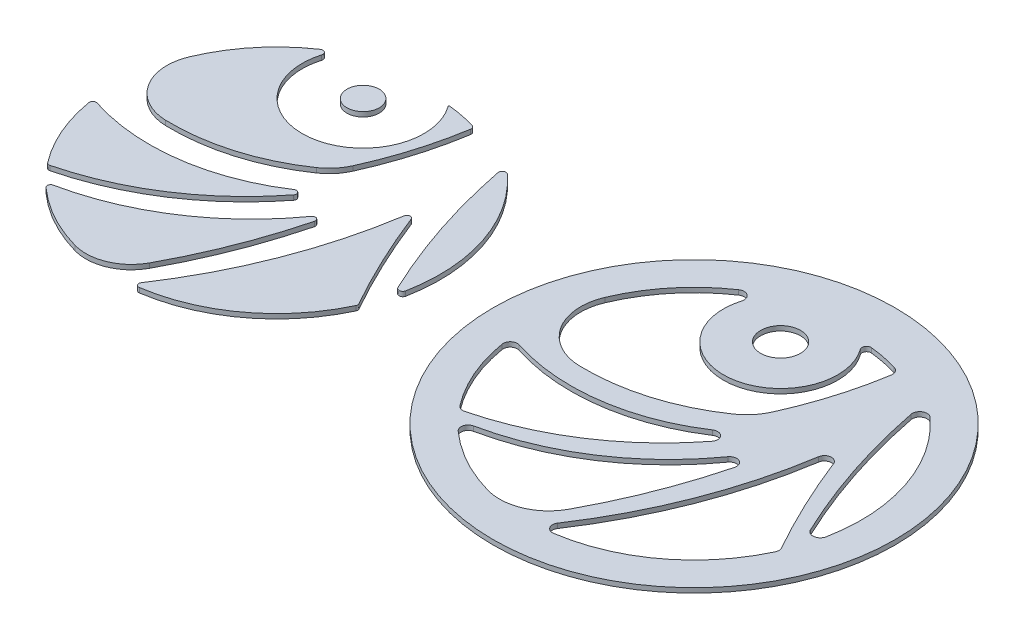
SolidWorks part; units mm, degrees
ref_plane "Front Plane" through (0, 0, 0) normal (0, 0, 1) x (1, 0, 0)
ref_plane "Top Plane" through (0, 0, 0) normal (0, 1, 0) x (1, 0, 0)
ref_plane "Right Plane" through (0, 0, 0) normal (1, 0, 0) x (0, 0, -1)
sketch "Sketch1" plane through (0, 0, 0) normal (0, 1, 0) x (1, 0, 0)
  line L0 (0, 0) -> (0, 6.0566) construction
  line L1 (44.4871, -0.2174) -> (44.4871, 5.8392) construction
  arc A34 (-4.7592, -16.858) -> (1.0322, -14.4089) centre (-3.3927, -12.0175) ccw construction
  arc A35 (11.8017, 12.9446) -> (17.1937, -3.3496) centre (0, 0) cw construction
  circle A36 centre (-2.9281, 12.0992) radius 1.9122 construction
  arc A37 (16.0926, -3.4891) -> (17.1937, -3.3496) centre (16.6201, -3.2378) ccw construction
  arc A38 (-8.936, 13.8547) -> (2.1496, 15.7589) centre (-2.9281, 12.0992) ccw construction
  arc A39 (10.8347, 12.3997) -> (16.0926, -3.4891) centre (76.7619, 25.4016) ccw construction
  arc A40 (-11.4052, -0.5681) -> (-16.15, 6.7839) centre (-11.2626, 4.731) cw construction
  arc A41 (2.9045, 5.3154) -> (5.7854, 14.9411) centre (-31.9799, 21.0002) ccw construction
  arc A42 (-11.4052, -0.5681) -> (1.0701, 3.1191) centre (-10.8394, 20.4655) ccw construction
  arc A43 (2.9045, 5.3154) -> (1.0701, 3.1191) centre (-1.9303, 7.4893) cw construction
  arc A44 (5.3743, 15.594) -> (2.3971, 16.1859) centre (0.6618, -0.327) ccw construction
  arc A45 (10.8347, 12.3997) -> (11.8017, 12.9446) centre (11.408, 12.5128) cw construction
  arc A46 (-8.936, 13.8547) -> (-9.8246, 14.5024) centre (-9.4969, 14.0186) ccw construction
  arc A47 (5.3743, 15.594) -> (5.7854, 14.9411) centre (5.2085, 15.0337) cw construction
  arc A48 (2.1496, 15.7589) -> (2.3971, 16.1859) centre (2.3689, 15.917) cw construction
  arc A49 (4.9905, -1.3518) -> (5.9661, -1.8054) centre (5.436, -1.6696) cw construction
  arc A50 (1.6673, 0.2398) -> (2.4003, -0.5531) centre (1.9681, -0.2174) cw construction
  arc A51 (10.8773, 3.6514) -> (9.8271, 3.5354) centre (10.3679, 3.4515) ccw construction
  arc A52 (15.8695, -6.8767) -> (15.8887, -7.3751) centre (15.3923, -7.1447) cw construction
  arc A53 (2.0596, -16.4793) -> (2.5965, -17.3234) centre (2.5154, -16.7822) ccw construction
  arc A54 (-11.4455, -12.0949) -> (-11.6987, -13.0378) centre (-11.3332, -12.6305) ccw construction
  arc A55 (-13.3427, -10.8431) -> (-13.9114, -10.6451) centre (-13.4768, -10.3125) cw construction
  arc A56 (-16.5773, -2.2267) -> (-17.2859, -2.8359) centre (-16.7458, -2.7473) ccw construction
  arc A57 (15.8887, -7.3751) -> (2.5965, -17.3234) centre (0, 0) cw construction
  arc A58 (-4.7592, -16.858) -> (-11.6987, -13.0378) centre (0, 0) cw construction
  arc A59 (-13.9114, -10.6451) -> (-17.2859, -2.8359) centre (0, 0) cw construction
  arc A60 (9.8271, 3.5354) -> (2.0596, -16.4793) centre (-39.5789, 11.1947) cw construction
  arc A61 (2.4003, -0.5531) -> (-13.3427, -10.8431) centre (-20.4231, 17.1773) cw construction
  arc A62 (1.6673, 0.2398) -> (-16.5773, -2.2267) centre (-10.0245, 18.0137) cw construction
  arc A63 (5.9661, -1.8054) -> (1.0322, -14.4089) centre (-47.7586, 11.959) cw construction
  arc A64 (4.9905, -1.3518) -> (-11.4455, -12.0949) centre (-16.9851, 14.3246) cw construction
  arc A65 (15.8695, -6.8767) -> (10.8773, 3.6514) centre (89.6755, 34.5677) cw construction
  arc A66 (-16.15, 6.7839) -> (-9.8246, 14.5024) centre (0, 0) cw construction
  arc A68 (39.7279, -17.0755) -> (45.5192, -14.6263) centre (41.0944, -12.235) ccw construction
  arc A69 (56.2888, 12.7272) -> (61.6808, -3.567) centre (44.4871, -0.2174) cw construction
  circle A70 centre (41.5589, 11.8818) radius 1.9122 construction
  arc A71 (60.5796, -3.7065) -> (61.6808, -3.567) centre (61.1072, -3.4553) ccw construction
  arc A72 (35.5511, 13.6373) -> (46.6366, 15.5415) centre (41.5589, 11.8818) ccw construction
  arc A73 (55.3218, 12.1823) -> (60.5796, -3.7065) centre (121.249, 25.1842) ccw construction
  arc A74 (33.0819, -0.7855) -> (28.3371, 6.5665) centre (33.2244, 4.5136) cw construction
  arc A75 (47.3916, 5.098) -> (50.2725, 14.7237) centre (12.5072, 20.7828) ccw construction
  arc A76 (33.0819, -0.7855) -> (45.5572, 2.9017) centre (33.6477, 20.2481) ccw construction
  arc A77 (47.3916, 5.098) -> (45.5572, 2.9017) centre (42.5568, 7.2719) cw construction
  arc A78 (49.8614, 15.3766) -> (46.8842, 15.9685) centre (45.1488, -0.5444) ccw construction
  arc A79 (55.3218, 12.1823) -> (56.2888, 12.7272) centre (55.8951, 12.2954) cw construction
  arc A80 (35.5511, 13.6373) -> (34.6625, 14.285) centre (34.9902, 13.8012) ccw construction
  arc A81 (49.8614, 15.3766) -> (50.2725, 14.7237) centre (49.6955, 14.8163) cw construction
  arc A82 (46.6366, 15.5415) -> (46.8842, 15.9685) centre (46.8559, 15.6996) cw construction
  arc A83 (49.4775, -1.5692) -> (50.4532, -2.0229) centre (49.923, -1.887) cw construction
  arc A84 (46.1544, 0.0224) -> (46.8873, -0.7706) centre (46.4552, -0.4348) cw construction
  arc A85 (55.3644, 3.434) -> (54.3142, 3.3179) centre (54.855, 3.2341) ccw construction
  arc A86 (60.3566, -7.0941) -> (60.3758, -7.5925) centre (59.8794, -7.3621) cw construction
  arc A87 (46.5467, -16.6967) -> (47.0836, -17.5409) centre (47.0025, -16.9996) ccw construction
  arc A88 (33.0415, -12.3123) -> (32.7884, -13.2552) centre (33.1538, -12.8479) ccw construction
  arc A89 (31.1444, -11.0605) -> (30.5757, -10.8625) centre (31.0103, -10.5299) cw construction
  arc A90 (27.9098, -2.4441) -> (27.2012, -3.0533) centre (27.7412, -2.9647) ccw construction
  arc A91 (60.3758, -7.5925) -> (47.0836, -17.5409) centre (44.4871, -0.2174) cw construction
  arc A92 (39.7279, -17.0755) -> (32.7884, -13.2552) centre (44.4871, -0.2174) cw construction
  arc A93 (30.5757, -10.8625) -> (27.2012, -3.0533) centre (44.4871, -0.2174) cw construction
  arc A94 (54.3142, 3.3179) -> (46.5467, -16.6967) centre (4.9081, 10.9773) cw construction
  arc A95 (46.8873, -0.7706) -> (31.1444, -11.0605) centre (24.064, 16.9599) cw construction
  arc A96 (46.1544, 0.0224) -> (27.9098, -2.4441) centre (34.4625, 17.7963) cw construction
  arc A97 (50.4532, -2.0229) -> (45.5192, -14.6263) centre (-3.2715, 11.7415) cw construction
  arc A98 (49.4775, -1.5692) -> (33.0415, -12.3123) centre (27.5019, 14.1072) cw construction
  arc A99 (60.3566, -7.0941) -> (55.3644, 3.434) centre (134.1625, 34.3503) cw construction
  arc A100 (28.3371, 6.5665) -> (34.6625, 14.285) centre (44.4871, -0.2174) cw construction
  circle A101 centre (44.4871, -0.2174) radius 21.3043
  arc A102 (39.6735, -17.2679) -> (45.6952, -14.7214) centre (41.0944, -12.235) ccw
  arc A103 (50.6469, -2.0725) -> (45.6952, -14.7214) centre (-3.2715, 11.7415) cw
  arc A104 (49.3147, -1.4531) -> (50.6469, -2.0725) centre (49.923, -1.887) cw
  arc A105 (49.3147, -1.4531) -> (33.0005, -12.1165) centre (27.5019, 14.1072) cw
  arc A106 (33.0005, -12.1165) -> (32.6548, -13.4041) centre (33.1538, -12.8479) ccw
  arc A107 (39.6735, -17.2679) -> (32.6548, -13.4041) centre (44.4871, -0.2174) cw
  arc A108 (56.4235, 12.875) -> (61.8771, -3.6052) centre (44.4871, -0.2174) cw
  arc A109 (60.399, -3.7925) -> (61.8771, -3.6052) centre (61.1072, -3.4553) ccw
  arc A110 (55.1256, 12.1436) -> (60.399, -3.7925) centre (121.249, 25.1842) ccw
  arc A111 (55.1256, 12.1436) -> (56.4235, 12.875) centre (55.8951, 12.2954) cw
  circle A112 centre (41.5589, 11.8818) radius 2.1122
  arc A113 (35.7431, 13.5812) -> (46.4744, 15.4246) centre (41.5589, 11.8818) ccw
  arc A114 (46.4744, 15.4246) -> (46.9051, 16.1674) centre (46.8559, 15.6996) cw
  arc A115 (49.9181, 15.5684) -> (46.9051, 16.1674) centre (45.1488, -0.5444) ccw
  arc A116 (49.9181, 15.5684) -> (50.47, 14.692) centre (49.6955, 14.8163) cw
  arc A117 (47.574, 5.016) -> (50.47, 14.692) centre (12.5072, 20.7828) ccw
  arc A118 (47.574, 5.016) -> (45.6704, 2.7368) centre (42.5568, 7.2719) cw
  arc A119 (33.0765, -0.9855) -> (45.6704, 2.7368) centre (33.6477, 20.2481) ccw
  arc A120 (33.0765, -0.9855) -> (28.1527, 6.644) centre (33.2244, 4.5136) cw
  arc A121 (28.1527, 6.644) -> (34.5503, 14.4506) centre (44.4871, -0.2174) cw
  arc A122 (35.7431, 13.5812) -> (34.5503, 14.4506) centre (34.9902, 13.8012) ccw
  arc A123 (46.0445, 0.1895) -> (47.0453, -0.8933) centre (46.4552, -0.4348) cw
  arc A124 (47.0453, -0.8933) -> (31.1934, -11.2544) centre (24.064, 16.9599) cw
  arc A125 (31.1934, -11.2544) -> (30.4169, -10.984) centre (31.0103, -10.5299) cw
  arc A126 (30.4169, -10.984) -> (27.0038, -3.0857) centre (44.4871, -0.2174) cw
  arc A127 (27.9714, -2.2538) -> (27.0038, -3.0857) centre (27.7412, -2.9647) ccw
  arc A128 (46.0445, 0.1895) -> (27.9714, -2.2538) centre (34.4625, 17.7963) cw
  arc A129 (55.5506, 3.507) -> (54.1165, 3.3486) centre (54.855, 3.2341) ccw
  arc A130 (54.1165, 3.3486) -> (46.3801, -16.586) centre (4.9081, 10.9773) cw
  arc A131 (46.3801, -16.586) -> (47.1132, -17.7386) centre (47.0025, -16.9996) ccw
  arc A132 (60.5572, -7.6767) -> (47.1132, -17.7386) centre (44.4871, -0.2174) cw
  arc A133 (60.531, -6.9962) -> (60.5572, -7.6767) centre (59.8794, -7.3621) cw
  arc A134 (60.531, -6.9962) -> (55.5506, 3.507) centre (134.1625, 34.3503) cw
  arc A135 (-4.732, -16.7618) -> (0.9442, -14.3613) centre (-3.3927, -12.0175) ccw construction
  arc A136 (5.8692, -1.7806) -> (0.9442, -14.3613) centre (-47.7586, 11.959) cw construction
  arc A137 (5.0719, -1.4099) -> (5.8692, -1.7806) centre (5.436, -1.6696) cw construction
  arc A138 (5.0719, -1.4099) -> (-11.425, -12.1927) centre (-16.9851, 14.3246) cw construction
  arc A139 (-11.425, -12.1927) -> (-11.6319, -12.9634) centre (-11.3332, -12.6305) ccw construction
  arc A140 (-4.732, -16.7618) -> (-11.6319, -12.9634) centre (0, 0) cw construction
  arc A141 (11.7344, 12.8707) -> (17.0956, -3.3305) centre (0, 0) cw construction
  arc A142 (16.1828, -3.4461) -> (17.0956, -3.3305) centre (16.6201, -3.2378) ccw construction
  arc A143 (10.9328, 12.4191) -> (16.1828, -3.4461) centre (76.7619, 25.4016) ccw construction
  arc A144 (10.9328, 12.4191) -> (11.7344, 12.8707) centre (11.408, 12.5128) cw construction
  circle A145 centre (-2.9281, 12.0992) radius 1.8122 construction
  arc A146 (-9.032, 13.8828) -> (2.2307, 15.8174) centre (-2.9281, 12.0992) ccw construction
  arc A147 (2.2307, 15.8174) -> (2.3867, 16.0864) centre (2.3689, 15.917) cw construction
  arc A148 (5.3459, 15.4981) -> (2.3867, 16.0864) centre (0.6618, -0.327) ccw construction
  arc A149 (5.3459, 15.4981) -> (5.6867, 14.9569) centre (5.2085, 15.0337) cw construction
  arc A150 (2.8133, 5.3565) -> (5.6867, 14.9569) centre (-31.9799, 21.0002) ccw construction
  arc A151 (2.8133, 5.3565) -> (1.0135, 3.2016) centre (-1.9303, 7.4893) cw construction
  arc A152 (-11.4025, -0.4682) -> (1.0135, 3.2016) centre (-10.8394, 20.4655) ccw construction
  arc A153 (-11.4025, -0.4682) -> (-16.0578, 6.7452) centre (-11.2626, 4.731) cw construction
  arc A154 (-16.0578, 6.7452) -> (-9.7685, 14.4196) centre (0, 0) cw construction
  arc A155 (-9.032, 13.8828) -> (-9.7685, 14.4196) centre (-9.4969, 14.0186) ccw construction
  arc A156 (1.7223, 0.1562) -> (2.3213, -0.4918) centre (1.9681, -0.2174) cw construction
  arc A157 (2.3213, -0.4918) -> (-13.3672, -10.7461) centre (-20.4231, 17.1773) cw construction
  arc A158 (-13.3672, -10.7461) -> (-13.832, -10.5843) centre (-13.4768, -10.3125) cw construction
  arc A159 (-13.832, -10.5843) -> (-17.1872, -2.8197) centre (0, 0) cw construction
  arc A160 (-16.6081, -2.3218) -> (-17.1872, -2.8197) centre (-16.7458, -2.7473) ccw construction
  arc A161 (1.7223, 0.1562) -> (-16.6081, -2.3218) centre (-10.0245, 18.0137) cw construction
  arc A162 (10.7843, 3.6149) -> (9.9259, 3.52) centre (10.3679, 3.4515) ccw construction
  arc A163 (9.9259, 3.52) -> (2.1429, -16.5347) centre (-39.5789, 11.1947) cw construction
  arc A164 (2.1429, -16.5347) -> (2.5817, -17.2245) centre (2.5154, -16.7822) ccw construction
  arc A165 (15.798, -7.333) -> (2.5817, -17.2245) centre (0, 0) cw construction
  arc A166 (15.7823, -6.9257) -> (15.798, -7.333) centre (15.3923, -7.1447) cw construction
  arc A167 (15.7823, -6.9257) -> (10.7843, 3.6149) centre (89.6755, 34.5677) cw construction
  arc A168 (-11.3998, -0.3682) -> (-15.9656, 6.7065) centre (-11.2626, 4.731) cw
  arc A169 (-15.9656, 6.7065) -> (-9.7124, 14.3369) centre (0, 0) cw
  arc A170 (-9.1279, 13.9108) -> (-9.7124, 14.3369) centre (-9.4969, 14.0186) ccw
  arc A171 (-9.1279, 13.9108) -> (2.3118, 15.8759) centre (-2.9281, 12.0992) ccw
  arc A172 (2.3118, 15.8759) -> (2.3762, 15.987) centre (2.3689, 15.917) cw
  arc A173 (5.3176, 15.4022) -> (2.3762, 15.987) centre (0.6618, -0.327) ccw
  arc A174 (5.3176, 15.4022) -> (5.588, 14.9728) centre (5.2085, 15.0337) cw
  arc A175 (2.7221, 5.3975) -> (5.588, 14.9728) centre (-31.9799, 21.0002) ccw
  arc A176 (2.7221, 5.3975) -> (0.9569, 3.284) centre (-1.9303, 7.4893) cw
  arc A177 (-11.3998, -0.3682) -> (0.9569, 3.284) centre (-10.8394, 20.4655) ccw
  arc A178 (1.7773, 0.0727) -> (-16.6389, -2.4169) centre (-10.0245, 18.0137) cw
  arc A179 (-16.6389, -2.4169) -> (-17.0885, -2.8035) centre (-16.7458, -2.7473) ccw
  arc A180 (-13.7525, -10.5235) -> (-17.0885, -2.8035) centre (0, 0) cw
  arc A181 (-13.3917, -10.6492) -> (-13.7525, -10.5235) centre (-13.4768, -10.3125) cw
  arc A182 (2.2423, -0.4304) -> (-13.3917, -10.6492) centre (-20.4231, 17.1773) cw
  arc A183 (1.7773, 0.0727) -> (2.2423, -0.4304) centre (1.9681, -0.2174) cw
  arc A184 (5.1533, -1.468) -> (-11.4045, -12.2906) centre (-16.9851, 14.3246) cw
  arc A185 (-11.4045, -12.2906) -> (-11.5651, -12.8889) centre (-11.3332, -12.6305) ccw
  arc A186 (-4.7049, -16.6656) -> (-11.5651, -12.8889) centre (0, 0) cw
  arc A187 (-4.7049, -16.6656) -> (0.8562, -14.3138) centre (-3.3927, -12.0175) ccw
  arc A188 (5.7724, -1.7558) -> (0.8562, -14.3138) centre (-47.7586, 11.959) cw
  arc A189 (5.1533, -1.468) -> (5.7724, -1.7558) centre (5.436, -1.6696) cw
  arc A190 (10.0247, 3.5047) -> (2.2262, -16.59) centre (-39.5789, 11.1947) cw
  arc A191 (2.2262, -16.59) -> (2.5669, -17.1257) centre (2.5154, -16.7822) ccw
  arc A192 (15.7073, -7.2909) -> (2.5669, -17.1257) centre (0, 0) cw
  arc A193 (15.6951, -6.9747) -> (15.7073, -7.2909) centre (15.3923, -7.1447) cw
  arc A194 (15.6951, -6.9747) -> (10.6912, 3.5783) centre (89.6755, 34.5677) cw
  arc A195 (10.6912, 3.5783) -> (10.0247, 3.5047) centre (10.3679, 3.4515) ccw
  arc A196 (11.0309, 12.4384) -> (16.2731, -3.4031) centre (76.7619, 25.4016) ccw
  arc A197 (16.2731, -3.4031) -> (16.9974, -3.3113) centre (16.6201, -3.2378) ccw
  arc A198 (11.667, 12.7968) -> (16.9974, -3.3113) centre (0, 0) cw
  arc A199 (11.0309, 12.4384) -> (11.667, 12.7968) centre (11.408, 12.5128) cw
  circle A200 centre (-2.9281, 12.0992) radius 1.7122
  point P63 (-17.4251, 1.791)
  point P64 (-0.7696, -17.5)
  point P65 (16.0055, -7.118)
  point P66 (-13.6898, -10.9285)
  point P67 (-8.9846, 15.0373)
  point P68 (1.7158, 17.4327)
  point P131 (27.0619, 1.5736)
  point P132 (43.7175, -17.7174)
  point P133 (60.4926, -7.3355)
  point P134 (30.7972, -11.1459)
  point P135 (35.5025, 14.8199)
  point P136 (46.2028, 17.2153)
  dimension "D1" = 5.0297
  dimension "D2" = 5.301
  dimension "D3" = 5.301
  dimension "D4" = 0.5844
  dimension "D5" = 0.2704
  dimension "D6" = 5.0297
  dimension "D7" = 5.301
  dimension "D8" = 5.301
  dimension "D9" = 0.5844
  dimension "D10" = 0.2704
  dimension "D11" = 0.2
  dimension "D12" = 0.1
  dimension "D13" = 0.1
extrude "Boss-Extrude1" add sketch "Sketch1" along normal blind 0.5
